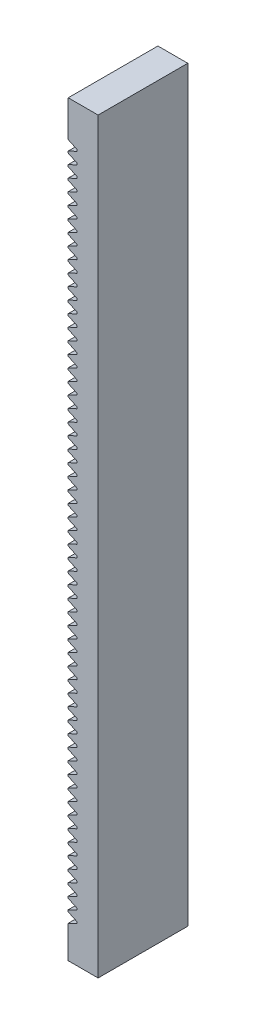
SolidWorks part; units mm, degrees
material "1060 Alloy"
ref_plane "Front Plane" through (0, 0, 0) normal (0, 0, 1) x (1, 0, 0)
ref_plane "Top Plane" through (0, 0, 0) normal (0, 1, 0) x (1, 0, 0)
ref_plane "Right Plane" through (0, 0, 0) normal (1, 0, 0) x (0, 0, -1)
sketch "Sketch1" plane through (0, 0, 0) normal (0, 0, 1) x (1, 0, 0)
  line L0 (-39.8025, 39.8025) -> (-39.8025, 30.1025)
  line L1 (-39.8025, 39.8025) -> (-31.8025, 39.8025)
  line L2 (-31.8025, -160.1975) -> (-31.8025, 39.8025)
  line L3 (-39.8025, -160.1975) -> (-31.8025, -160.1975)
  line L5 (-39.8025, -145.7375) -> (-37.5025, -146.8075)
  line L7 (-39.8025, 30.1025) -> (-37.5025, 29.0325)
  line L8 (-39.8025, -151.5175) -> (-39.8025, -160.1975)
  line L9 (-39.8025, -145.2375) -> (-39.8025, -145.7375)
  line L10 (-39.8025, -142.5975) -> (-37.5025, -143.6675)
  line L11 (-39.8025, -145.2375) -> (-37.5025, -144.1675)
  line L12 (-37.5025, -149.9475) -> (-37.5025, -150.4475)
  line L13 (-39.8025, -148.3775) -> (-39.8025, -148.8775)
  line L14 (-37.5025, -143.6675) -> (-37.5025, -144.1675)
  line L15 (-39.8025, -142.0975) -> (-39.8025, -142.5975)
  line L16 (-37.5025, -146.8075) -> (-37.5025, -147.3075)
  line L17 (-39.8025, -139.4575) -> (-37.5025, -140.5275)
  line L18 (-39.8025, -142.0975) -> (-37.5025, -141.0275)
  line L19 (-39.8025, -148.8775) -> (-37.5025, -149.9475)
  line L20 (-39.8025, -148.3775) -> (-37.5025, -147.3075)
  line L21 (-39.8025, -151.5175) -> (-37.5025, -150.4475)
  line L22 (-37.5025, -140.5275) -> (-37.5025, -141.0275)
  line L23 (-39.8025, -138.9575) -> (-39.8025, -139.4575)
  line L24 (-39.8025, -136.3175) -> (-37.5025, -137.3875)
  line L25 (-39.8025, -138.9575) -> (-37.5025, -137.8875)
  line L26 (-37.5025, -137.3875) -> (-37.5025, -137.8875)
  line L27 (-39.8025, -135.8175) -> (-39.8025, -136.3175)
  line L28 (-39.8025, -133.1775) -> (-37.5025, -134.2475)
  line L29 (-39.8025, -135.8175) -> (-37.5025, -134.7475)
  line L30 (-37.5025, -134.2475) -> (-37.5025, -134.7475)
  line L31 (-39.8025, -132.6775) -> (-39.8025, -133.1775)
  line L32 (-39.8025, -130.0375) -> (-37.5025, -131.1075)
  line L33 (-39.8025, -132.6775) -> (-37.5025, -131.6075)
  line L34 (-37.5025, -131.1075) -> (-37.5025, -131.6075)
  line L35 (-39.8025, -129.5375) -> (-39.8025, -130.0375)
  line L36 (-39.8025, -126.8975) -> (-37.5025, -127.9675)
  line L37 (-39.8025, -129.5375) -> (-37.5025, -128.4675)
  line L38 (-37.5025, -127.9675) -> (-37.5025, -128.4675)
  line L39 (-39.8025, -126.3975) -> (-39.8025, -126.8975)
  line L40 (-39.8025, -123.7575) -> (-37.5025, -124.8275)
  line L41 (-39.8025, -126.3975) -> (-37.5025, -125.3275)
  line L42 (-37.5025, -124.8275) -> (-37.5025, -125.3275)
  line L43 (-39.8025, -123.2575) -> (-39.8025, -123.7575)
  line L44 (-39.8025, -120.6175) -> (-37.5025, -121.6875)
  line L45 (-39.8025, -123.2575) -> (-37.5025, -122.1875)
  line L46 (-37.5025, -121.6875) -> (-37.5025, -122.1875)
  line L47 (-39.8025, -120.1175) -> (-39.8025, -120.6175)
  line L48 (-39.8025, -117.4775) -> (-37.5025, -118.5475)
  line L49 (-39.8025, -120.1175) -> (-37.5025, -119.0475)
  line L50 (-37.5025, -118.5475) -> (-37.5025, -119.0475)
  line L51 (-39.8025, -116.9775) -> (-39.8025, -117.4775)
  line L52 (-39.8025, -114.3375) -> (-37.5025, -115.4075)
  line L53 (-39.8025, -116.9775) -> (-37.5025, -115.9075)
  line L54 (-37.5025, -115.4075) -> (-37.5025, -115.9075)
  line L55 (-39.8025, -113.8375) -> (-39.8025, -114.3375)
  line L56 (-39.8025, -111.1975) -> (-37.5025, -112.2675)
  line L57 (-39.8025, -113.8375) -> (-37.5025, -112.7675)
  line L58 (-37.5025, -112.2675) -> (-37.5025, -112.7675)
  line L59 (-39.8025, -110.6975) -> (-39.8025, -111.1975)
  line L60 (-39.8025, -108.0575) -> (-37.5025, -109.1275)
  line L61 (-39.8025, -110.6975) -> (-37.5025, -109.6275)
  line L62 (-37.5025, -109.1275) -> (-37.5025, -109.6275)
  line L63 (-39.8025, -107.5575) -> (-39.8025, -108.0575)
  line L64 (-39.8025, -104.9175) -> (-37.5025, -105.9875)
  line L65 (-39.8025, -107.5575) -> (-37.5025, -106.4875)
  line L66 (-37.5025, -105.9875) -> (-37.5025, -106.4875)
  line L67 (-39.8025, -104.4175) -> (-39.8025, -104.9175)
  line L68 (-39.8025, -101.7775) -> (-37.5025, -102.8475)
  line L69 (-39.8025, -104.4175) -> (-37.5025, -103.3475)
  line L70 (-37.5025, -102.8475) -> (-37.5025, -103.3475)
  line L71 (-39.8025, -101.2775) -> (-39.8025, -101.7775)
  line L72 (-39.8025, -98.6375) -> (-37.5025, -99.7075)
  line L73 (-39.8025, -101.2775) -> (-37.5025, -100.2075)
  line L74 (-37.5025, -99.7075) -> (-37.5025, -100.2075)
  line L75 (-39.8025, -98.1375) -> (-39.8025, -98.6375)
  line L76 (-39.8025, -95.4975) -> (-37.5025, -96.5675)
  line L77 (-39.8025, -98.1375) -> (-37.5025, -97.0675)
  line L78 (-37.5025, -96.5675) -> (-37.5025, -97.0675)
  line L79 (-39.8025, -94.9975) -> (-39.8025, -95.4975)
  line L80 (-39.8025, -92.3575) -> (-37.5025, -93.4275)
  line L81 (-39.8025, -94.9975) -> (-37.5025, -93.9275)
  line L82 (-37.5025, -93.4275) -> (-37.5025, -93.9275)
  line L83 (-39.8025, -91.8575) -> (-39.8025, -92.3575)
  line L84 (-39.8025, -89.2175) -> (-37.5025, -90.2875)
  line L85 (-39.8025, -91.8575) -> (-37.5025, -90.7875)
  line L86 (-37.5025, -90.2875) -> (-37.5025, -90.7875)
  line L87 (-39.8025, -88.7175) -> (-39.8025, -89.2175)
  line L88 (-39.8025, -86.0775) -> (-37.5025, -87.1475)
  line L89 (-39.8025, -88.7175) -> (-37.5025, -87.6475)
  line L90 (-37.5025, -87.1475) -> (-37.5025, -87.6475)
  line L91 (-39.8025, -85.5775) -> (-39.8025, -86.0775)
  line L92 (-39.8025, -82.9375) -> (-37.5025, -84.0075)
  line L93 (-39.8025, -85.5775) -> (-37.5025, -84.5075)
  line L94 (-37.5025, -84.0075) -> (-37.5025, -84.5075)
  line L95 (-39.8025, -82.4375) -> (-39.8025, -82.9375)
  line L96 (-39.8025, -79.7975) -> (-37.5025, -80.8675)
  line L97 (-39.8025, -82.4375) -> (-37.5025, -81.3675)
  line L98 (-37.5025, -80.8675) -> (-37.5025, -81.3675)
  line L99 (-39.8025, -79.2975) -> (-39.8025, -79.7975)
  line L100 (-39.8025, -76.6575) -> (-37.5025, -77.7275)
  line L101 (-39.8025, -79.2975) -> (-37.5025, -78.2275)
  line L102 (-37.5025, -77.7275) -> (-37.5025, -78.2275)
  line L103 (-39.8025, -76.1575) -> (-39.8025, -76.6575)
  line L104 (-39.8025, -73.5175) -> (-37.5025, -74.5875)
  line L105 (-39.8025, -76.1575) -> (-37.5025, -75.0875)
  line L106 (-37.5025, -74.5875) -> (-37.5025, -75.0875)
  line L107 (-39.8025, -73.0175) -> (-39.8025, -73.5175)
  line L108 (-39.8025, -70.3775) -> (-37.5025, -71.4475)
  line L109 (-39.8025, -73.0175) -> (-37.5025, -71.9475)
  line L110 (-37.5025, -71.4475) -> (-37.5025, -71.9475)
  line L111 (-39.8025, -69.8775) -> (-39.8025, -70.3775)
  line L112 (-39.8025, -67.2375) -> (-37.5025, -68.3075)
  line L113 (-39.8025, -69.8775) -> (-37.5025, -68.8075)
  line L114 (-37.5025, -68.3075) -> (-37.5025, -68.8075)
  line L115 (-39.8025, -66.7375) -> (-39.8025, -67.2375)
  line L116 (-39.8025, -64.0975) -> (-37.5025, -65.1675)
  line L117 (-39.8025, -66.7375) -> (-37.5025, -65.6675)
  line L118 (-37.5025, -65.1675) -> (-37.5025, -65.6675)
  line L119 (-39.8025, -63.5975) -> (-39.8025, -64.0975)
  line L120 (-39.8025, -60.9575) -> (-37.5025, -62.0275)
  line L121 (-39.8025, -63.5975) -> (-37.5025, -62.5275)
  line L122 (-37.5025, -62.0275) -> (-37.5025, -62.5275)
  line L123 (-39.8025, -60.4575) -> (-39.8025, -60.9575)
  line L124 (-39.8025, -57.8175) -> (-37.5025, -58.8875)
  line L125 (-39.8025, -60.4575) -> (-37.5025, -59.3875)
  line L126 (-37.5025, -58.8875) -> (-37.5025, -59.3875)
  line L127 (-39.8025, -57.3175) -> (-39.8025, -57.8175)
  line L128 (-39.8025, -54.6775) -> (-37.5025, -55.7475)
  line L129 (-39.8025, -57.3175) -> (-37.5025, -56.2475)
  line L130 (-37.5025, -55.7475) -> (-37.5025, -56.2475)
  line L131 (-39.8025, -54.1775) -> (-39.8025, -54.6775)
  line L132 (-39.8025, -51.5375) -> (-37.5025, -52.6075)
  line L133 (-39.8025, -54.1775) -> (-37.5025, -53.1075)
  line L134 (-37.5025, -52.6075) -> (-37.5025, -53.1075)
  line L135 (-39.8025, -51.0375) -> (-39.8025, -51.5375)
  line L136 (-39.8025, -48.3975) -> (-37.5025, -49.4675)
  line L137 (-39.8025, -51.0375) -> (-37.5025, -49.9675)
  line L138 (-37.5025, -49.4675) -> (-37.5025, -49.9675)
  line L139 (-39.8025, -47.8975) -> (-39.8025, -48.3975)
  line L140 (-39.8025, -45.2575) -> (-37.5025, -46.3275)
  line L141 (-39.8025, -47.8975) -> (-37.5025, -46.8275)
  line L142 (-37.5025, -46.3275) -> (-37.5025, -46.8275)
  line L143 (-39.8025, -44.7575) -> (-39.8025, -45.2575)
  line L144 (-39.8025, -42.1175) -> (-37.5025, -43.1875)
  line L145 (-39.8025, -44.7575) -> (-37.5025, -43.6875)
  line L146 (-37.5025, -43.1875) -> (-37.5025, -43.6875)
  line L147 (-39.8025, -41.6175) -> (-39.8025, -42.1175)
  line L148 (-39.8025, -38.9775) -> (-37.5025, -40.0475)
  line L149 (-39.8025, -41.6175) -> (-37.5025, -40.5475)
  line L150 (-37.5025, -40.0475) -> (-37.5025, -40.5475)
  line L151 (-39.8025, -38.4775) -> (-39.8025, -38.9775)
  line L152 (-39.8025, -35.8375) -> (-37.5025, -36.9075)
  line L153 (-39.8025, -38.4775) -> (-37.5025, -37.4075)
  line L154 (-37.5025, -36.9075) -> (-37.5025, -37.4075)
  line L155 (-39.8025, -35.3375) -> (-39.8025, -35.8375)
  line L156 (-39.8025, -32.6975) -> (-37.5025, -33.7675)
  line L157 (-39.8025, -35.3375) -> (-37.5025, -34.2675)
  line L158 (-37.5025, -33.7675) -> (-37.5025, -34.2675)
  line L159 (-39.8025, -32.1975) -> (-39.8025, -32.6975)
  line L160 (-39.8025, -29.5575) -> (-37.5025, -30.6275)
  line L161 (-39.8025, -32.1975) -> (-37.5025, -31.1275)
  line L162 (-37.5025, -30.6275) -> (-37.5025, -31.1275)
  line L163 (-39.8025, -29.0575) -> (-39.8025, -29.5575)
  line L164 (-39.8025, -26.4175) -> (-37.5025, -27.4875)
  line L165 (-39.8025, -29.0575) -> (-37.5025, -27.9875)
  line L166 (-37.5025, -27.4875) -> (-37.5025, -27.9875)
  line L167 (-39.8025, -25.9175) -> (-39.8025, -26.4175)
  line L168 (-39.8025, -23.2775) -> (-37.5025, -24.3475)
  line L169 (-39.8025, -25.9175) -> (-37.5025, -24.8475)
  line L170 (-37.5025, -24.3475) -> (-37.5025, -24.8475)
  line L171 (-39.8025, -22.7775) -> (-39.8025, -23.2775)
  line L172 (-39.8025, -20.1375) -> (-37.5025, -21.2075)
  line L173 (-39.8025, -22.7775) -> (-37.5025, -21.7075)
  line L174 (-37.5025, -21.2075) -> (-37.5025, -21.7075)
  line L175 (-39.8025, -19.6375) -> (-39.8025, -20.1375)
  line L176 (-39.8025, -16.9975) -> (-37.5025, -18.0675)
  line L177 (-39.8025, -19.6375) -> (-37.5025, -18.5675)
  line L178 (-37.5025, -18.0675) -> (-37.5025, -18.5675)
  line L179 (-39.8025, -16.4975) -> (-39.8025, -16.9975)
  line L180 (-39.8025, -13.8575) -> (-37.5025, -14.9275)
  line L181 (-39.8025, -16.4975) -> (-37.5025, -15.4275)
  line L182 (-37.5025, -14.9275) -> (-37.5025, -15.4275)
  line L183 (-39.8025, -13.3575) -> (-39.8025, -13.8575)
  line L184 (-39.8025, -10.7175) -> (-37.5025, -11.7875)
  line L185 (-39.8025, -13.3575) -> (-37.5025, -12.2875)
  line L186 (-37.5025, -11.7875) -> (-37.5025, -12.2875)
  line L187 (-39.8025, -10.2175) -> (-39.8025, -10.7175)
  line L188 (-39.8025, -7.5775) -> (-37.5025, -8.6475)
  line L189 (-39.8025, -10.2175) -> (-37.5025, -9.1475)
  line L190 (-37.5025, -8.6475) -> (-37.5025, -9.1475)
  line L191 (-39.8025, -7.0775) -> (-39.8025, -7.5775)
  line L192 (-39.8025, -4.4375) -> (-37.5025, -5.5075)
  line L193 (-39.8025, -7.0775) -> (-37.5025, -6.0075)
  line L194 (-37.5025, -5.5075) -> (-37.5025, -6.0075)
  line L195 (-39.8025, -3.9375) -> (-39.8025, -4.4375)
  line L196 (-39.8025, -1.2975) -> (-37.5025, -2.3675)
  line L197 (-39.8025, -3.9375) -> (-37.5025, -2.8675)
  line L198 (-37.5025, -2.3675) -> (-37.5025, -2.8675)
  line L199 (-39.8025, -0.7975) -> (-39.8025, -1.2975)
  line L200 (-39.8025, 1.8425) -> (-37.5025, 0.7725)
  line L201 (-39.8025, -0.7975) -> (-37.5025, 0.2725)
  line L202 (-37.5025, 0.7725) -> (-37.5025, 0.2725)
  line L203 (-39.8025, 2.3425) -> (-39.8025, 1.8425)
  line L204 (-39.8025, 4.9825) -> (-37.5025, 3.9125)
  line L205 (-39.8025, 2.3425) -> (-37.5025, 3.4125)
  line L206 (-37.5025, 3.9125) -> (-37.5025, 3.4125)
  line L207 (-39.8025, 5.4825) -> (-39.8025, 4.9825)
  line L208 (-39.8025, 8.1225) -> (-37.5025, 7.0525)
  line L209 (-39.8025, 5.4825) -> (-37.5025, 6.5525)
  line L210 (-37.5025, 7.0525) -> (-37.5025, 6.5525)
  line L211 (-39.8025, 8.6225) -> (-39.8025, 8.1225)
  line L212 (-39.8025, 11.2625) -> (-37.5025, 10.1925)
  line L213 (-39.8025, 8.6225) -> (-37.5025, 9.6925)
  line L214 (-37.5025, 10.1925) -> (-37.5025, 9.6925)
  line L215 (-39.8025, 11.7625) -> (-39.8025, 11.2625)
  line L216 (-39.8025, 14.4025) -> (-37.5025, 13.3325)
  line L217 (-39.8025, 11.7625) -> (-37.5025, 12.8325)
  line L218 (-37.5025, 13.3325) -> (-37.5025, 12.8325)
  line L219 (-39.8025, 14.9025) -> (-39.8025, 14.4025)
  line L220 (-39.8025, 17.5425) -> (-37.5025, 16.4725)
  line L221 (-39.8025, 14.9025) -> (-37.5025, 15.9725)
  line L222 (-37.5025, 16.4725) -> (-37.5025, 15.9725)
  line L223 (-39.8025, 18.0425) -> (-39.8025, 17.5425)
  line L224 (-39.8025, 20.6825) -> (-37.5025, 19.6125)
  line L225 (-39.8025, 18.0425) -> (-37.5025, 19.1125)
  line L226 (-37.5025, 19.6125) -> (-37.5025, 19.1125)
  line L227 (-39.8025, 21.1825) -> (-39.8025, 20.6825)
  line L228 (-39.8025, 23.8225) -> (-37.5025, 22.7525)
  line L229 (-39.8025, 21.1825) -> (-37.5025, 22.2525)
  line L230 (-37.5025, 22.7525) -> (-37.5025, 22.2525)
  line L231 (-39.8025, 27.4625) -> (-37.5025, 28.5325)
  line L232 (-39.8025, 26.9625) -> (-37.5025, 25.8925)
  line L233 (-39.8025, 24.3225) -> (-39.8025, 23.8225) [skipped]
  line L234 (-37.5025, -146.8075) -> (-37.5025, -147.3075) [skipped]
  line L235 (-39.8025, -148.3775) -> (-37.5025, -147.3075) [skipped]
  line L236 (-39.8025, 24.3225) -> (-37.5025, 25.3925)
  line L237 (-39.8025, 24.3225) -> (-39.8025, 23.8225)
  line L238 (-37.5025, 25.8925) -> (-37.5025, 25.3925)
  line L239 (-39.8025, 27.4625) -> (-39.8025, 26.9625)
  line L240 (-37.5025, 29.0325) -> (-37.5025, 28.5325)
  line L243 (-39.8025, 33.2425) -> (-37.5025, 32.1725) [skipped]
  line L244 (-39.8025, 30.6025) -> (-37.5025, 31.6725) [skipped]
  line L245 (-37.5025, 32.1725) -> (-37.5025, 31.6725) [skipped]
  line L246 (-39.8025, 30.6025) -> (-39.8025, 30.1025) [skipped]
  dimension "D1" = 8
  dimension "D2" = 200
  dimension "D3" = 9.42
  dimension "D5" = 90
  dimension "D4" = 90
  dimension "D6" = 90
  dimension "D7" = 90
extrude "Extrude1" add sketch "Sketch1" against normal blind 24
